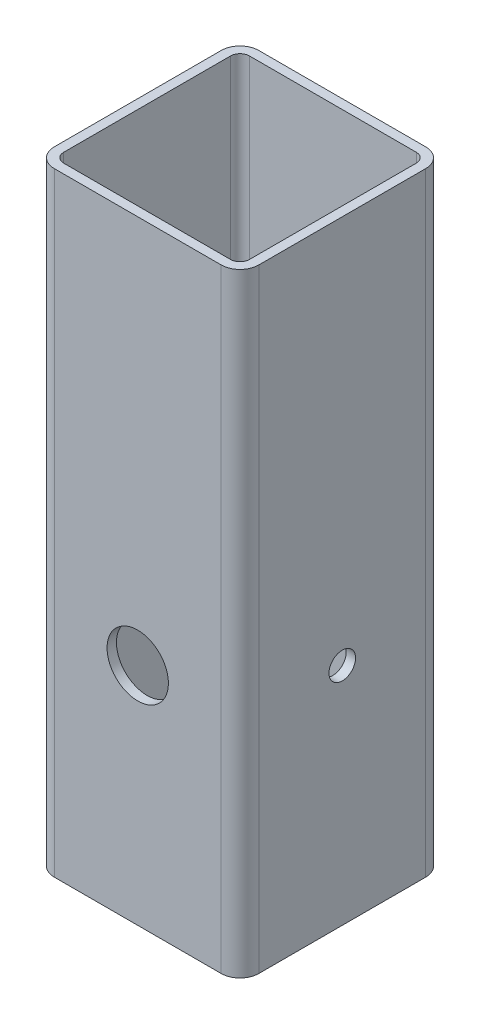
SolidWorks part; units mm, degrees
ref_plane "Front Plane" through (0, 0, 0) normal (0, 0, 1) x (1, 0, 0)
ref_plane "Top Plane" through (0, 0, 0) normal (0, 1, 0) x (1, 0, 0)
ref_plane "Right Plane" through (0, 0, 0) normal (1, 0, 0) x (0, 0, -1)
sketch "Sketch1" plane through (0, 0, 0) normal (1, 0, 0) x (0, 0, -1)
  line L0 (0, -75) -> (0, 75)
  point P4 (0, 0)
  dimension "D1" = 150
other "Shs c450 as 50X50X2.3 SHS C450(1)"
ref_plane "Plane1" through (0, -75, 0) normal (0, 1, 0) x (0, 0, 1)
sketch "Sketch11" plane through (0, -75, 0) normal (0, 1, 0) x (0, 0, 1)
  line L0 (-20.4, 22.7) -> (20.4, 22.7)
  line L1 (-20.4, -25) -> (20.4, -25)
  line L2 (-25, -20.4) -> (-25, 20.4)
  line L3 (-20.4, 25) -> (20.4, 25)
  line L4 (25, -20.4) -> (25, 20.4)
  line L5 (-25, -25) -> (25, 25) construction
  line L6 (-25, 25) -> (25, -25) construction
  line L7 (22.7, -20.4) -> (22.7, 20.4)
  line L8 (-20.4, -22.7) -> (20.4, -22.7)
  line L9 (-22.7, -20.4) -> (-22.7, 20.4)
  arc A0 (-25, 20.4) -> (-20.4, 25) centre (-20.4, 20.4) cw
  arc A1 (20.4, 25) -> (25, 20.4) centre (20.4, 20.4) cw
  arc A2 (-20.4, -25) -> (-25, -20.4) centre (-20.4, -20.4) cw
  arc A3 (20.4, -25) -> (25, -20.4) centre (20.4, -20.4) ccw
  arc A4 (-22.7, 20.4) -> (-20.4, 22.7) centre (-20.4, 20.4) cw
  arc A5 (20.4, 22.7) -> (22.7, 20.4) centre (20.4, 20.4) cw
  arc A6 (20.4, -22.7) -> (22.7, -20.4) centre (20.4, -20.4) ccw
  arc A7 (-20.4, -22.7) -> (-22.7, -20.4) centre (-20.4, -20.4) cw
  point P0 (0, 0)
  point P30 (-25, 0)
  point P31 (0, 25)
  point P32 (25, 0)
  point P33 (0, -25)
  point P34 (0, 0)
  dimension "D2" = 4.6
  dimension "Thickness" = 2.3
  dimension "Width" = 50
sketch "Sketch12" plane through (25, 0, 0) normal (1, 0, 0) x (0, 0, -1)
  line L0 (0, 0) -> (0, -20) construction
  line L1 (-20.4, -75) -> (20.4, -75) construction
  circle A0 centre (0, -20) radius 3.25
  dimension "D1" = 6.5
  dimension "D2" = 55
extrude "Cut-Extrude1" cut sketch "Sketch12" against normal blind 10
sketch "Sketch13" plane through (0, 0, -25) normal (0, 0, -1) x (-1, 0, 0)
  line L0 (0, -20) -> (0, 0) construction
  line L1 (-20.4, -75) -> (20.4, -75) construction
  circle A0 centre (0, -20) radius 3.25
  dimension "D1" = 6.5
  dimension "D2" = 55
extrude "Cut-Extrude2" cut sketch "Sketch13" against normal blind 10
sketch "Sketch14" plane through (0, 0, 25) normal (0, 0, 1) x (1, 0, 0)
  circle A0 centre (0, -20) radius 7.5
  dimension "D1" = 15
extrude "Cut-Extrude3" cut sketch "Sketch14" against normal blind 10
sketch "Sketch15" plane through (-25, 0, 0) normal (-1, 0, 0) x (0, 0, 1)
  circle A0 centre (0, -20) radius 7.5
  dimension "D1" = 15
extrude "Cut-Extrude4" cut sketch "Sketch15" against normal blind 10
